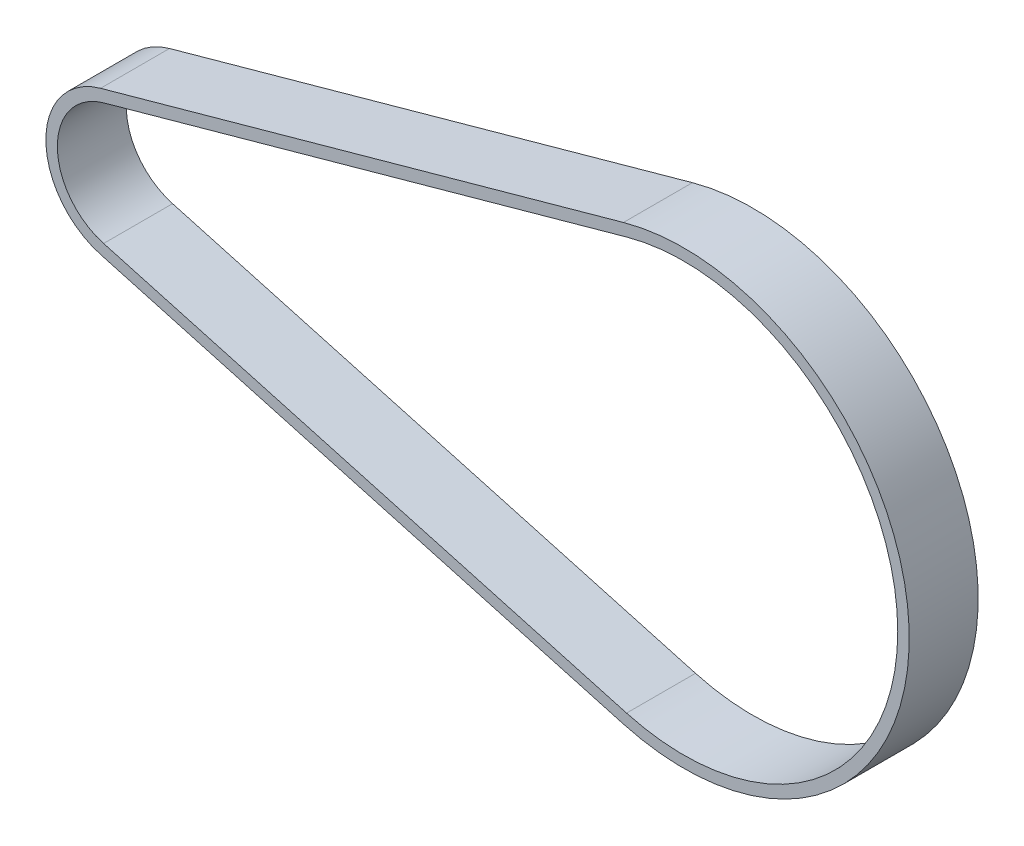
SolidWorks part; units mm, degrees
material "HYPALON"
ref_plane "Alzado" through (0, 0, 0) normal (0, 0, 1) x (1, 0, 0)
ref_plane "Planta" through (0, 0, 0) normal (0, 1, 0) x (1, 0, 0)
ref_plane "Vista lateral" through (0, 0, 0) normal (1, 0, 0) x (0, 0, -1)
sketch "Croquis1" plane through (0, 0, 0) normal (0, 0, 1) x (1, 0, 0)
  line L0 (-1.4721, 5.2993) -> (44.0364, 17.9407)
  line L1 (-1.4721, -5.2993) -> (44.0364, -17.9407)
  line L2 (-1.7397, 6.2629) -> (43.7688, 18.9042)
  line L3 (-1.7397, -6.2629) -> (43.7688, -18.9042)
  arc A0 (-1.4721, 5.2993) -> (-1.4721, -5.2993) centre (0, 0) ccw
  arc A1 (44.0364, -17.9407) -> (44.0364, 17.9407) centre (49.02, 0) ccw
  arc A2 (43.7688, -18.9042) -> (43.7688, 18.9042) centre (49.02, 0) ccw
  arc A3 (-1.7397, 6.2629) -> (-1.7397, -6.2629) centre (0, 0) ccw
  dimension "D1" = 11
  dimension "D2" = 37.24
  dimension "D3" = 49.02
  dimension "D4" = 1
extrude "Saliente-Extruir1" add sketch "Croquis1" along normal blind 6
